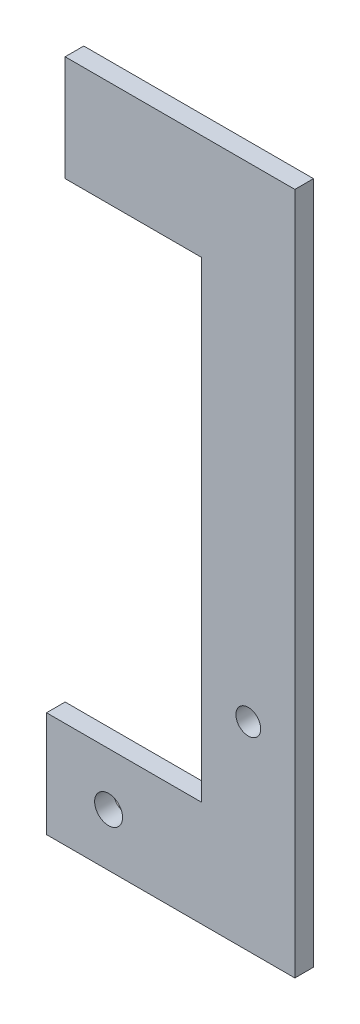
SolidWorks part; units mm, degrees
ref_plane "Front Plane" through (0, 0, 0) normal (0, 0, 1) x (1, 0, 0)
ref_plane "Top Plane" through (0, 0, 0) normal (0, 1, 0) x (1, 0, 0)
ref_plane "Right Plane" through (0, 0, 0) normal (1, 0, 0) x (0, 0, -1)
sketch "Croquis1" plane through (0, 0, 0) normal (0, 0, 1) x (1, 0, 0)
  line L0 (0, 0) -> (40, 0)
  line L1 (40, 0) -> (40, 110)
  line L2 (40, 110) -> (23, 110)
  line L3 (25, 93) -> (25, 17)
  line L4 (25, 17) -> (0, 17)
  line L5 (0, 17) -> (0, 0)
  line L6 (25, 17) -> (40, 0) construction
  line L7 (0, 8.5) -> (10, 8.5) construction
  line L8 (23, 110) -> (3, 110)
  line L9 (3, 110) -> (3, 93)
  line L10 (3, 93) -> (25, 93)
  line L11 (25, 32) -> (40, 32) construction
  circle A0 centre (10, 8.5) radius 2.25
  circle A1 centre (32.5, 32) radius 2
  dimension "D4" = 4.5
  dimension "D8" = 4
  dimension "D1" = 40
  dimension "D2" = 110
  dimension "D3" = 17
  dimension "D5" = 10
  dimension "D6" = 20
  dimension "D7" = 15
  dimension "D9" = 32
extrude "Saliente-Extruir1" add sketch "Croquis1" along normal blind 3 contours L5 L0 L1 L2 L8 L9 L10 L3 L4 | A0 | A1
